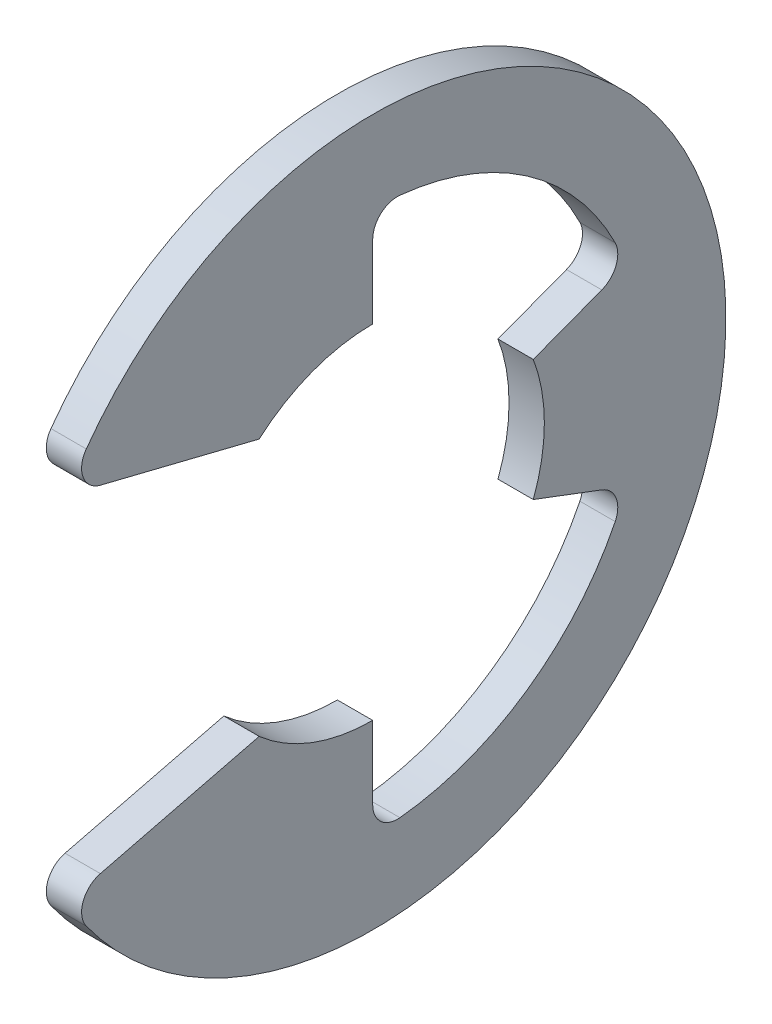
SolidWorks part; units mm, degrees
ref_plane "Front" through (0, 0, 0) normal (0, 0, 1) x (1, 0, 0)
ref_plane "Top" through (0, 0, 0) normal (0, 1, 0) x (1, 0, 0)
ref_plane "Right" through (0, 0, 0) normal (1, 0, 0) x (0, 0, -1)
sketch "Sketch1" plane through (0, 0, 0) normal (1, 0, 0) x (0, 0, -1)
  line L0 (-5.5002, -3.1733) -> (-2.0413, -2.3146)
  line L1 (-5.5002, 3.1733) -> (-2.0413, 2.3146)
  line L2 (0, -3.0861) -> (0, -4.8702)
  line L3 (0, 3.0861) -> (0, 4.8702)
  line L4 (2.8868, -1.0911) -> (4.5557, -1.7219)
  line L5 (2.8868, 1.0911) -> (4.5557, 1.7219)
  line L6 (0, 0) -> (-6.604, 0) construction
  line L7 (2.8868, 1.0911) -> (2.8868, -1.0911) construction
  line L8 (0, -3.0861) -> (-2.0413, -2.3146) construction
  line L9 (0, 6.35) -> (0, -6.35) construction
  circle A1 centre (0, 0) radius 6.604 construction
  circle A2 centre (0, 0) radius 3.0861 construction
  arc A3 (-5.5002, -3.1733) -> (-5.5002, 3.1733) centre (0, 0) ccw
  arc A4 (-2.0413, -2.3146) -> (0, -3.0861) centre (0, 0) ccw
  arc A5 (-2.0413, 2.3146) -> (0, 3.0861) centre (0, 0) cw
  arc A6 (2.8868, 1.0911) -> (2.8868, -1.0911) centre (0, 0) cw
  arc A7 (0, -4.8702) -> (4.5557, -1.7219) centre (0, 0) ccw
  arc A8 (4.5557, 1.7219) -> (0, 4.8702) centre (0, 0) ccw
  dimension "D" = 6.1722
  dimension "D1" = 4.8702
  dimension "OD" = 12.7
  dimension "D2" = 3.5091
  dimension "D3" = 4.6292
extrude "Extrude1" add sketch "Sketch1" along normal mid plane 0.635
fillet "Fillet1" radius 0.4445 6 edges at (0, -4.8702, 0) (0, 4.8702, 0) (0, -3.1733, 5.5002) (0, 3.1733, 5.5002) (0, -1.7219, -4.5557) (0, 1.7219, -4.5557)
sketch "Sketch3" plane through (0, 0, 0) normal (0, 1, 0) x (1, 0, 0)
  line L0 (0.3683, 3.9624) -> (0.3683, 3.175)
  line L1 (0.3683, 3.175) -> (-0.3683, 3.175)
  line L2 (-0.3683, 3.175) -> (-0.3683, 3.9624)
  line L3 (-0.3683, 3.9624) -> (-7.9185, 3.9624)
  line L4 (3.1306, 0) -> (3.1306, 3.5687)
  line L5 (-7.9185, 3.9624) -> (-7.9185, 0)
  line L6 (-7.9185, 0) -> (3.1306, 0)
  line L8 (3.1306, 0) -> (3.1306, 3.9624) construction
  line L9 (3.1306, 3.9624) -> (0.3683, 3.9624) construction
  line L10 (3.1306, 0) -> (17.2631, 0) construction
  line L11 (3.1306, 3.5687) -> (2.7368, 3.9624)
  line L12 (2.7368, 3.9624) -> (0.3683, 3.9624)
  point P2 (0, 3.175)
  point P5 (0.3683, 3.5687)
  dimension "D2" = 11.049
  dimension "D1" = 2.7622
  dimension "D3" = 45
revolve "Revolve2" [suppressed] add sketch "Sketch3" angle 360 about L10
equation "\"D2@Sketch3\" = \"W@Sketch3\"*15"
equation "\"D1@Sketch3\" = \"D2@Sketch3\"/4"
equation "\"D1@Sketch1\" = (\"OD@Sketch1\"+\"D@Sketch1\")/3.875"
equation "\"D3@Sketch1\" = \"D@Sketch1\"*.75"
equation "\"D1@Fillet1\" = \"D1@Extrude1\"*.7"
